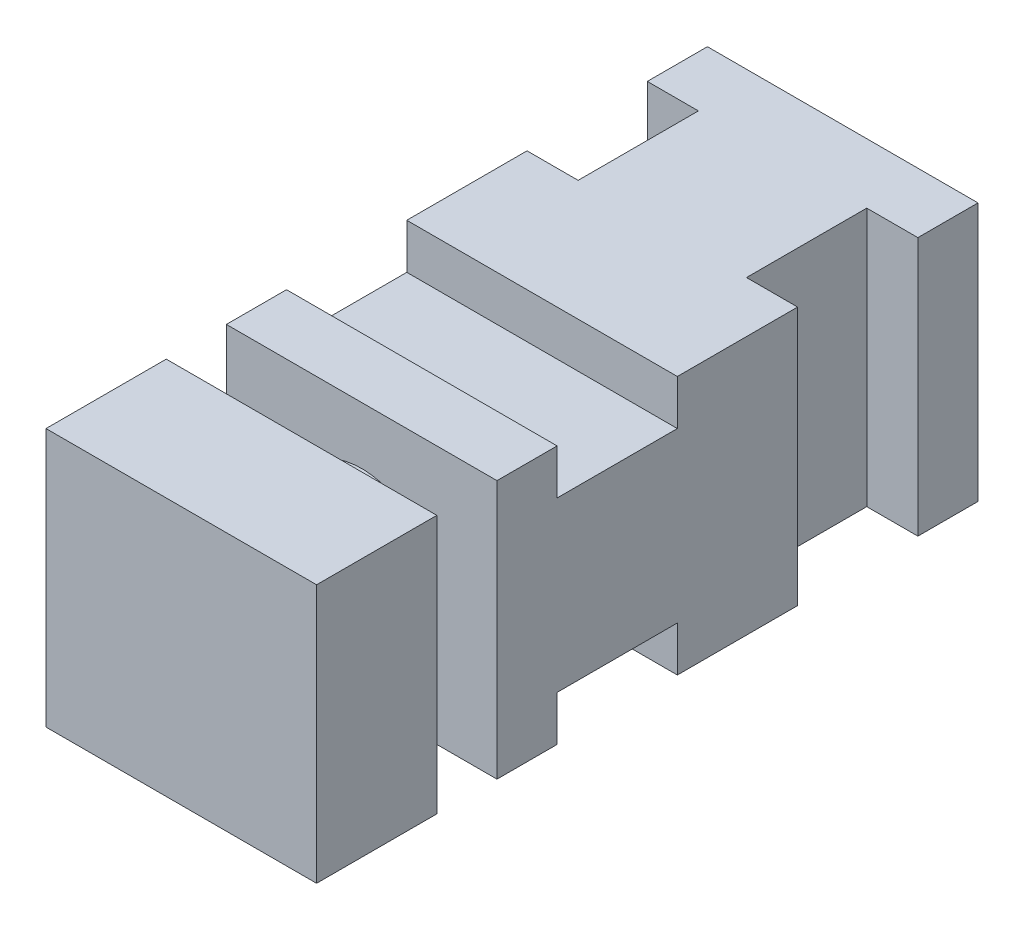
SolidWorks part; units mm, degrees
ref_plane "前视基准面" through (0, 0, 0) normal (0, 0, 1) x (1, 0, 0)
ref_plane "上视基准面" through (0, 0, 0) normal (0, 1, 0) x (1, 0, 0)
ref_plane "右视基准面" through (0, 0, 0) normal (1, 0, 0) x (0, 0, -1)
sketch "草图2" plane through (0, 0, 0) normal (0, 0, 1) x (1, 0, 0)
  line L9 (-1.125, -1.075) -> (1.125, -1.075)
  line L10 (-1.125, -1.075) -> (-1.125, 1.075)
  line L11 (-1.125, 1.075) -> (1.125, 1.075)
  line L12 (1.125, -1.075) -> (1.125, 1.075)
  line L13 (-1.125, -1.075) -> (1.125, 1.075) construction
  line L14 (-1.125, 1.075) -> (1.125, -1.075) construction
  point P0 (0, 0)
  dimension "D1" = 2.15
  dimension "D2" = 2.25
extrude "凸台-拉伸4" add sketch "草图2" along normal blind 1
sketch "草图4" plane through (0, 0, 0) normal (0, 0, -1) x (-1, 0, 0)
  circle A0 centre (0, 0) radius 0.6
  dimension "D1" = 1.2
extrude "凸台-拉伸5" add sketch "草图4" along normal blind 0.5
sketch "草图5" plane through (0, 0, -0.5) normal (0, 0, -1) x (-1, 0, 0)
  line L1 (-1.125, -1.075) -> (1.125, -1.075)
  line L2 (-1.125, -1.075) -> (-1.125, 1.075)
  line L3 (-1.125, 1.075) -> (1.125, 1.075)
  line L4 (1.125, -1.075) -> (1.125, 1.075)
  line L5 (-1.125, -1.075) -> (1.125, 1.075) construction
  line L6 (-1.125, 1.075) -> (1.125, -1.075) construction
  point P0 (0, 0)
  dimension "D1" = 2.15
  dimension "D2" = 2.25
extrude "凸台-拉伸6" add sketch "草图5" along normal blind 2
sketch "草图6" plane through (-1.125, 0, 0) normal (-1, 0, 0) x (0, 0, 1)
  line L0 (-0.5, 0) -> (-2.5, 0) construction
  line L1 (-0.5, -0.6) -> (-0.5, 0.6) construction
  line L2 (-2.5, -1.075) -> (-2.5, 1.075) construction
  line L3 (-1.5, -1.075) -> (-1.5, 1.075) construction
  line L4 (-2.5, 1.075) -> (-0.5, 1.075) construction
  line L5 (-2, 1.075) -> (-1, 1.075)
  line L6 (-1, 1.075) -> (-1, 0.7)
  line L7 (-1, 0.7) -> (-2, 0.7)
  line L8 (-1.5, 0.7) -> (-1.5, 1.075)
  line L9 (-2, 1.075) -> (-2, 0.7)
  line L10 (-1, 1.075) -> (-1, 0.7)
  line L11 (-2, 1.075) -> (-2, 0.7)
  line L12 (-2, -1.075) -> (-2, -0.7)
  line L13 (-1, -1.075) -> (-1, -0.7)
  line L14 (-2, -1.075) -> (-2, -0.7)
  line L15 (-1.5, -0.7) -> (-1.5, -1.075)
  line L16 (-1, -0.7) -> (-2, -0.7)
  line L17 (-1, -1.075) -> (-1, -0.7)
  line L18 (-2, -1.075) -> (-1, -1.075)
  line L19 (-2, 1.075) -> (-1, 1.075)
  line L20 (-2, -1.075) -> (-1, -1.075)
  point P16 (-1.5, 0)
  line M7 (-0.5, 1.075) -> (-2.5, 1.075)
  line M9 (-2.5, -1.075) -> (-0.5, -1.075)
  dimension "D1" = 1
  dimension "D2" = 1.4
extrude "切除-拉伸1" cut sketch "草图6" against normal through all both and the other way through all contours L15 L16 L12 M9 | L13 L16 L15 M9 | L5 L9 L7 L8 | L8 L7 L6 M7
sketch "草图7" plane through (0, 0, -2.5) normal (0, 0, -1) x (-1, 0, 0)
  line L1 (-1.125, -1.075) -> (1.125, -1.075)
  line L2 (-1.125, -1.075) -> (-1.125, 1.075)
  line L3 (-1.125, 1.075) -> (1.125, 1.075)
  line L4 (1.125, -1.075) -> (1.125, 1.075)
  line L5 (-1.125, -1.075) -> (1.125, 1.075) construction
  line L6 (-1.125, 1.075) -> (1.125, -1.075) construction
  point P0 (0, 0)
extrude "凸台-拉伸7" add sketch "草图7" along normal blind 2
sketch "草图9" plane through (0, -1.075, 0) normal (0, -1, 0) x (1, 0, 0)
  line L0 (-1.125, -4.5) -> (-1.125, -2.5) construction
  line L1 (-1.125, -4.5) -> (-1.125, -2) construction
  line L2 (-1.125, -3.5) -> (1.125, -3.5) construction
  line L3 (1.125, -4.5) -> (1.125, -2) construction
  line L4 (-1.125, -4) -> (-1.125, -3)
  line L5 (-1.125, -3) -> (-0.7, -3)
  line L6 (-0.7, -3) -> (-0.7, -4)
  line L7 (-1.125, -4) -> (-0.7, -4)
  line L8 (0, -4.5) -> (0, -3.0885) construction
  line L9 (1.125, -4.5) -> (-1.125, -4.5) construction
  line L10 (1.125, -4) -> (0.7, -4)
  line L11 (0.7, -3) -> (0.7, -4)
  line L12 (1.125, -3) -> (0.7, -3)
  line L13 (1.125, -4) -> (1.125, -3)
  point P13 (-0.7, -3.5)
  point P23 (0.7, -3.5)
  dimension "D1" = 2
  dimension "D2" = 1.4
  dimension "D3" = 1
extrude "切除-拉伸2" cut sketch "草图9" against normal through all both and the other way through all
